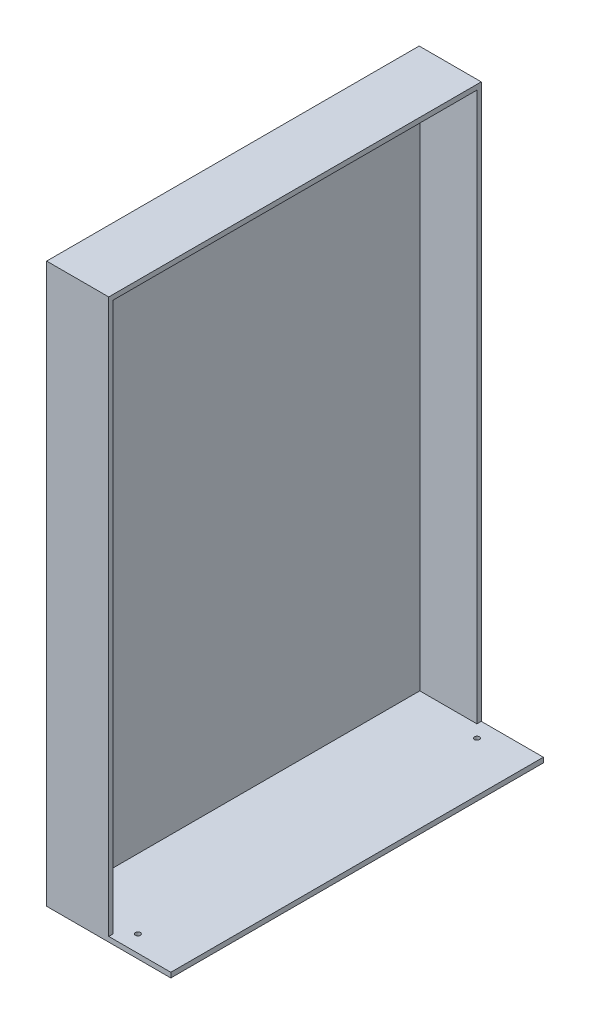
SolidWorks part; units mm, degrees
material "有机玻璃 (TM) GS 丙烯酸铸钣"
ref_plane "前视基准面" through (0, 0, 0) normal (0, 0, 1) x (1, 0, 0)
ref_plane "上视基准面" through (0, 0, 0) normal (0, 1, 0) x (1, 0, 0)
ref_plane "右视基准面" through (0, 0, 0) normal (1, 0, 0) x (0, 0, -1)
sketch "草图1" plane through (0, 0, 0) normal (0, 1, 0) x (1, 0, 0)
  line L1 (0, 0) -> (100, 0)
  line L2 (0, 0) -> (0, 300)
  line L3 (0, 300) -> (100, 300)
  line L4 (100, 0) -> (100, 300)
  dimension "D1" = 100
  dimension "D2" = 300
extrude "凸台-拉伸1" add sketch "草图1" along normal blind 4
sketch "草图2" plane through (0, 4, 0) normal (0, 1, 0) x (1, 0, 0)
  line L0 (100, 300) -> (0, 300) construction
  line L1 (0, 0) -> (8.236, 0)
  line L2 (0, 0) -> (0, 300)
  line L3 (0, 300) -> (8.236, 300)
  line L4 (4, 3.5) -> (4, 296.5)
  line L6 (8.236, 300) -> (50, 300)
  line L8 (4, 296.5) -> (50, 296.5)
  line L9 (50, 300) -> (50, 296.5)
  line L10 (8.236, 0) -> (50, 0)
  line L12 (4, 3.5) -> (50, 3.5)
  line L13 (50, 0) -> (50, 3.5)
  dimension "D1" = 3.5
  dimension "D2" = 3.5
  dimension "D3" = 4
  dimension "D4" = 50
extrude "凸台-拉伸2" add sketch "草图2" along normal blind 442
sketch "草图3" plane through (0, 446, 0) normal (0, 1, 0) x (1, 0, 0)
  line L1 (0, 0) -> (50, 0)
  line L2 (0, 0) -> (0, 300)
  line L3 (0, 300) -> (50, 300)
  line L4 (50, 0) -> (50, 300)
extrude "凸台-拉伸3" add sketch "草图3" along normal blind 4
hole_wizard "Ø4.0 (4) 直径孔1" positions "草图5" profile "草图4" hole size "Ø4.0" standard "GB" end condition through all
sketch "草图5" plane through (0, 0, 0) normal (0, -1, 0) x (-1, 0, 0)
  line L0 (0, 300) -> (0, 0) construction
  line L1 (-100, 300) -> (0, 300) construction
  line L2 (0, 0) -> (-100, 0) construction
  point P0 (-60, 13.5)
  point P2 (-60, 286.5)
  dimension "D1" = 60
  dimension "D2" = 13.5
  dimension "D3" = 13.5
sketch "草图4" plane through (60, 0, -13.5) normal (1, 0, 0) x (0, 0, -1)
  line L0 (0, 0) -> (0, 450)
  line L1 (0, 450) -> (2, 450)
  line L2 (2, 450) -> (2, 0)
  line L5 (2, 0) -> (0, 0)
  line L11 (0, -6.35) -> (0, 107.95) construction
  dimension "通孔孔直径" = 4
  dimension "通孔孔深度" = 450
